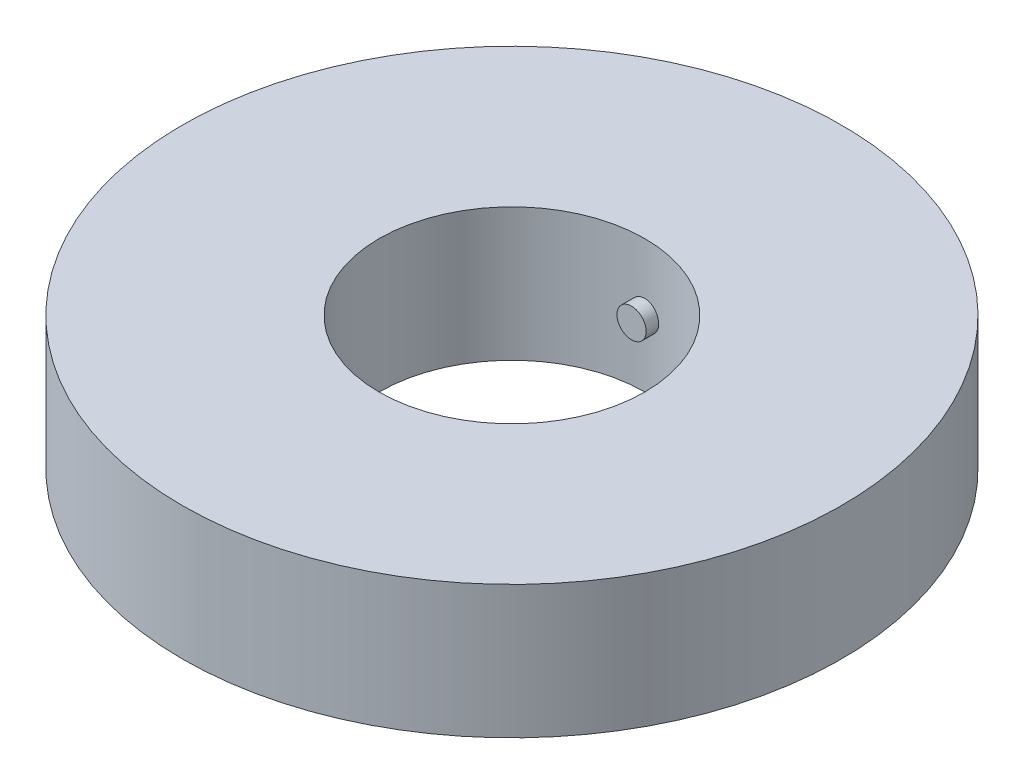
SolidWorks part; units mm, degrees
material "Epoxy, Unfilled"
ref_plane "Front Plane" through (0, 0, 0) normal (0, 0, 1) x (1, 0, 0)
ref_plane "Top Plane" through (0, 0, 0) normal (0, 1, 0) x (1, 0, 0)
ref_plane "Right Plane" through (0, 0, 0) normal (1, 0, 0) x (0, 0, -1)
sketch "Sketch1" plane through (0, 0, 0) normal (0, 1, 0) x (1, 0, 0)
  circle A0 centre (0, 0) radius 31.496
  circle A1 centre (0, 0) radius 12.7
  dimension "D1" = 62.992
  dimension "D2" = 25.4
extrude "Boss-Extrude1" add sketch "Sketch1" along normal blind 12.7
ref_plane "Plane1" through (0, 0, -12.7) normal (0, 0, 1) x (1, 0, 0)
sketch "Sketch3" plane through (0, 0, -12.7) normal (0, 0, 1) x (1, 0, 0)
  line L0 (-31.496, 12.7) -> (-31.496, 0) construction
  line L1 (-31.496, 12.7) -> (-31.496, 0)
  circle A0 centre (0, 6.35) radius 1.397
  point P13 (-31.496, 6.35)
  dimension "D1" = 2.794
extrude "Boss-Extrude2" add sketch "Sketch3" along normal blind 1.27 and the other way blind 5.08 contours A0
mirror "Mirror1" about plane through (0, 0, 0) normal (0, 0, 1) of "Boss-Extrude2"
